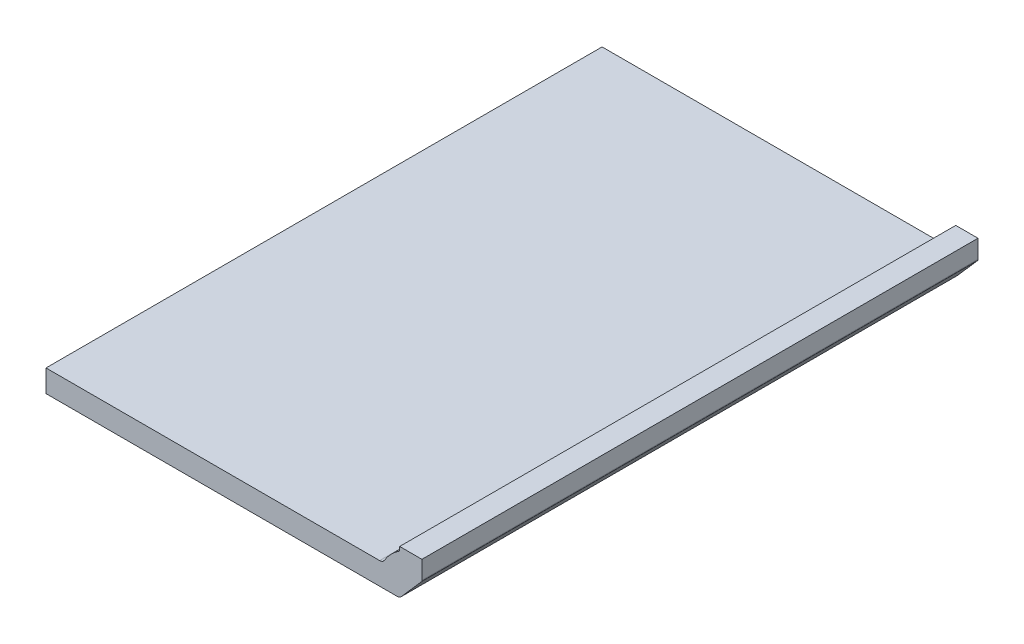
SolidWorks part; units mm, degrees
ref_plane "Front Plane" through (0, 0, 0) normal (0, 0, 1) x (1, 0, 0)
ref_plane "Top Plane" through (0, 0, 0) normal (0, 1, 0) x (1, 0, 0)
ref_plane "Right Plane" through (0, 0, 0) normal (1, 0, 0) x (0, 0, -1)
sketch "Sketch1" plane through (0, 0, 0) normal (0, 0, 1) x (1, 0, 0)
  line L0 (-0.2265, 0) -> (-31.8, 0)
  line L2 (-31.8, 2) -> (-1.7976, 2)
  line L3 (0.1494, 0.1703) -> (1.9504, 2.2238)
  line L4 (2, 2.3556) -> (2, 4)
  line L5 (-31.8, 2) -> (-31.8, 0)
  line L7 (2, 4) -> (0, 4)
  line L9 (0, 4) -> (0, 3.7417)
  arc A0 (-1.7976, 2) -> (-1.3707, 2.2396) centre (-1.7976, 2.5) ccw
  arc A1 (1.9504, 2.2238) -> (2, 2.3556) centre (1.8, 2.3556) ccw
  arc A2 (0, 3.7417) -> (-0.0889, 3.5754) centre (-0.2, 3.7417) cw
  arc A3 (0.1494, 0.1703) -> (-0.2265, 0) centre (-0.2265, 0.5) cw
  arc A6 (-0.0889, 3.5754) -> (-1.3707, 2.2396) centre (2.3, 0) ccw
  point P17 (0, 0)
  dimension "D3" = 0.2
  dimension "D1" = 0.5
  dimension "D2" = 0.2
  dimension "D4" = 0.5
extrude "Boss-Extrude1" add sketch "Sketch1" against normal blind 50
